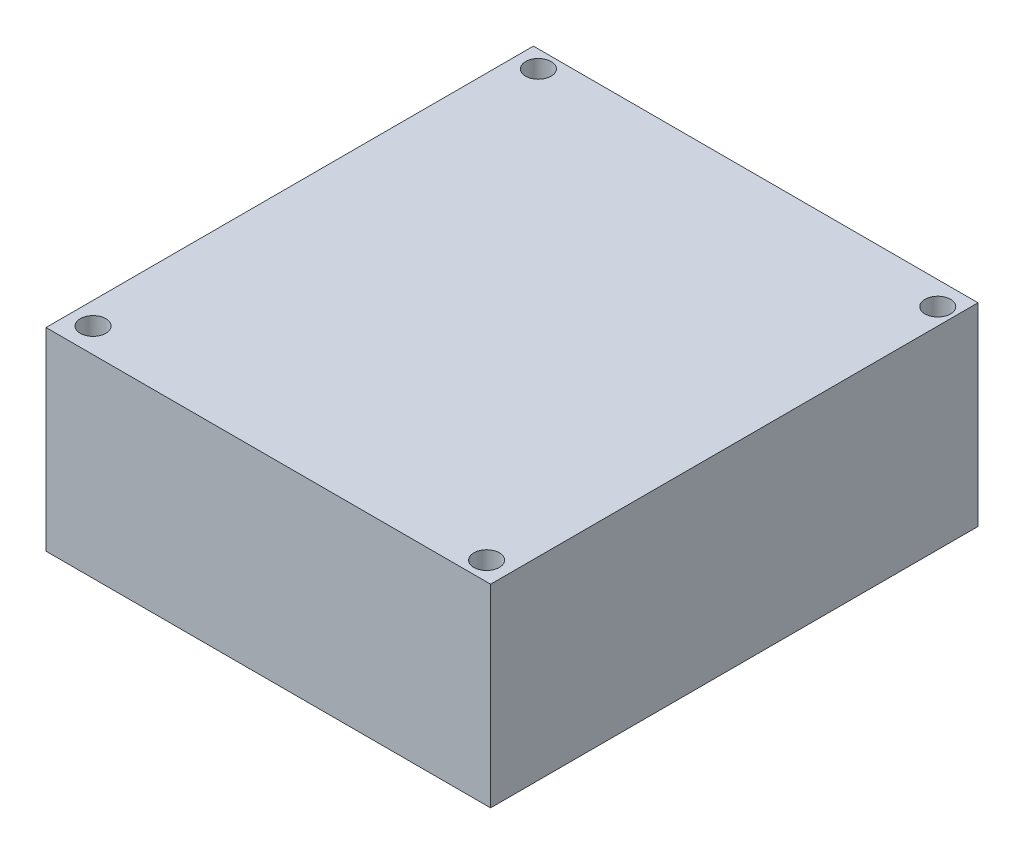
SolidWorks part; units mm, degrees
material "Epoxy, renforcé"
ref_plane "Plan de face" through (0, 0, 0) normal (0, 0, 1) x (1, 0, 0)
ref_plane "Plan de dessus" through (0, 0, 0) normal (0, 1, 0) x (1, 0, 0)
ref_plane "Plan de droite" through (0, 0, 0) normal (1, 0, 0) x (0, 0, -1)
sketch "Esquisse1" plane through (0, 0, 0) normal (0, 1, 0) x (1, 0, 0)
  line L1 (0, 0) -> (43.6, 0)
  line L2 (0, 0) -> (0, 47.8)
  line L3 (0, 47.8) -> (43.6, 47.8)
  line L4 (43.6, 0) -> (43.6, 47.8)
  dimension "D1" = 47.8
  dimension "D2" = 43.6
extrude "Boss.-Extru.1" add sketch "Esquisse1" along normal blind 19
sketch "Esquisse2" plane through (0, 19, 0) normal (0, 1, 0) x (1, 0, 0)
  circle A0 centre (2.1776, 46.1111) radius 1.25
  circle A1 centre (41.9522, 45.502) radius 1.25
  circle A2 centre (41.3611, 1.8484) radius 1.25
  circle A3 centre (2.1776, 2.4359) radius 1.25
  dimension "D1" = 2.5
extrude "Enlèv. mat.-Extru.1" cut sketch "Esquisse2" against normal through all
